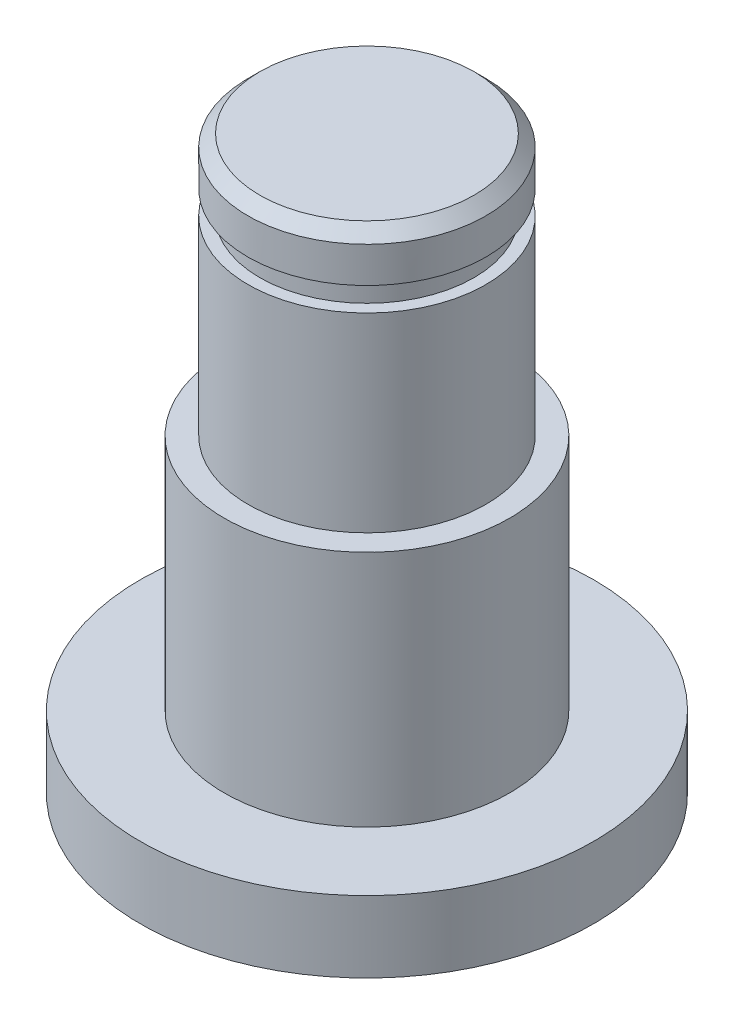
SolidWorks part; units mm, degrees
material "AISI 1020"
ref_plane "Alzado" through (0, 0, 0) normal (0, 0, 1) x (1, 0, 0)
ref_plane "Planta" through (0, 0, 0) normal (0, 1, 0) x (1, 0, 0)
ref_plane "Vista lateral" through (0, 0, 0) normal (1, 0, 0) x (0, 0, -1)
sketch "Croquis1" plane through (0, 0, 0) normal (0, 0, 1) x (1, 0, 0)
  line L0 (0, 0) -> (0, 44.5779) construction
  line L1 (0, 0) -> (-9.525, 0)
  line L2 (-9.525, 0) -> (-9.525, 3)
  line L3 (-9.525, 3) -> (-6, 3)
  line L4 (-6, 3) -> (-6, 13)
  line L5 (-6, 13) -> (-5, 13)
  line L6 (-5, 13) -> (-5, 24)
  line L7 (-5, 24) -> (0, 24)
  line L8 (0, 24) -> (0, 0)
  dimension "D1" = 5
  dimension "D2" = 1
  dimension "D3" = 9.525
  dimension "D4" = 3
  dimension "D5" = 10
  dimension "D6" = 11
revolve "Revolución1" add sketch "Croquis1" angle 360 about L0
sketch "Croquis2" plane through (0, 0, 0) normal (0, 0, 1) x (1, 0, 0)
  line L0 (5, 13) -> (5, 24) construction
  line L1 (4.5, 22) -> (5.5, 22)
  line L2 (4.5, 22) -> (4.5, 21)
  line L3 (4.5, 21) -> (5.5, 21)
  line L4 (5.5, 22) -> (5.5, 21)
  line L5 (4.5, 22) -> (5.5, 21) construction
  line L6 (4.5, 21) -> (5.5, 22) construction
  line L7 (6, 13) -> (-6, 13) construction
  line L8 (0, 0) -> (0, 30.4182) construction
  point P0 (5, 21.5)
  dimension "D1" = 1
  dimension "D2" = 8
revolve "Cortar-Revolución1" cut sketch "Croquis2" angle 360 about L8
chamfer "Chaflán1" distance 0.5 angle 45 1 edges at (0, 24, -5)
